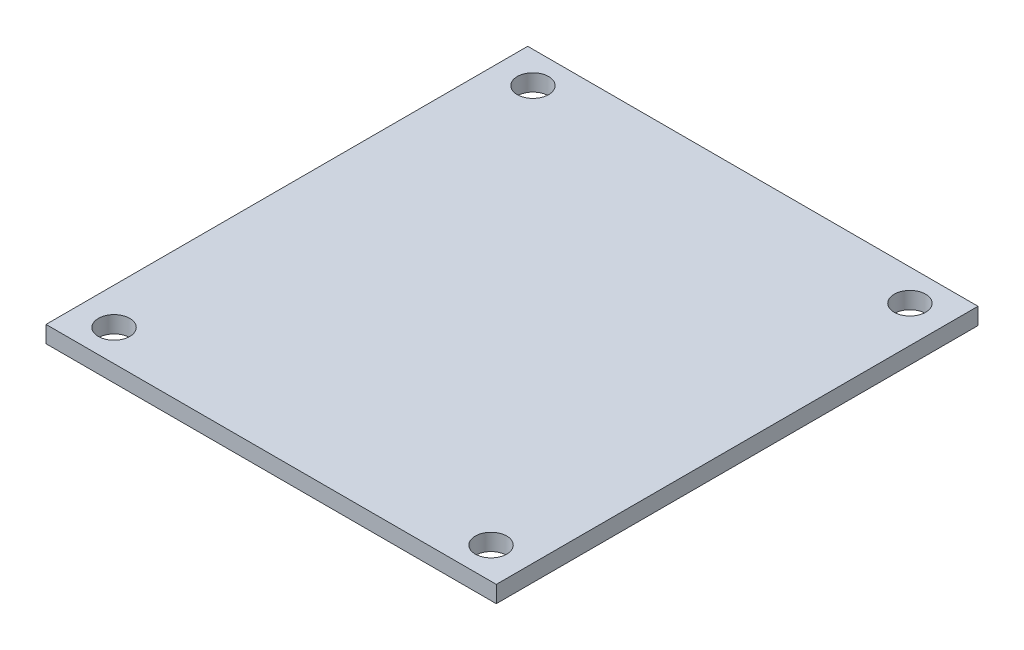
SolidWorks part; units mm, degrees
ref_plane "Plan de face" through (0, 0, 0) normal (0, 0, 1) x (1, 0, 0)
ref_plane "Plan de dessus" through (0, 0, 0) normal (0, 1, 0) x (1, 0, 0)
ref_plane "Plan de droite" through (0, 0, 0) normal (1, 0, 0) x (0, 0, -1)
sketch "Esquisse1" plane through (0, 0, 0) normal (0, 1, 0) x (1, 0, 0)
  line L1 (-21.5, 23) -> (21.5, 23)
  line L2 (-21.5, 23) -> (-21.5, -23)
  line L3 (-21.5, -23) -> (21.5, -23)
  line L4 (21.5, 23) -> (21.5, -23)
  line L5 (-21.5, 23) -> (21.5, -23) construction
  line L6 (-21.5, -23) -> (21.5, 23) construction
  circle A0 centre (-18, 20) radius 1.5
  circle A1 centre (18, 20) radius 1.5
  circle A2 centre (18, -20) radius 1.5
  circle A3 centre (-18, -20) radius 1.5
  point P0 (0, 0)
  point P16 (4.4502, -1.5803)
  dimension "D3" = 3
  dimension "D4" = 3
  dimension "D5" = 3
  dimension "D6" = 3
  dimension "D1" = 46
  dimension "D2" = 43
  dimension "D7" = 36
  dimension "D8" = 36
  dimension "D9" = 40
  dimension "D10" = 3
  dimension "D11" = 3.5
  dimension "D12" = 3
extrude "Boss.-Extru.1" add sketch "Esquisse1" along normal blind 1.6
